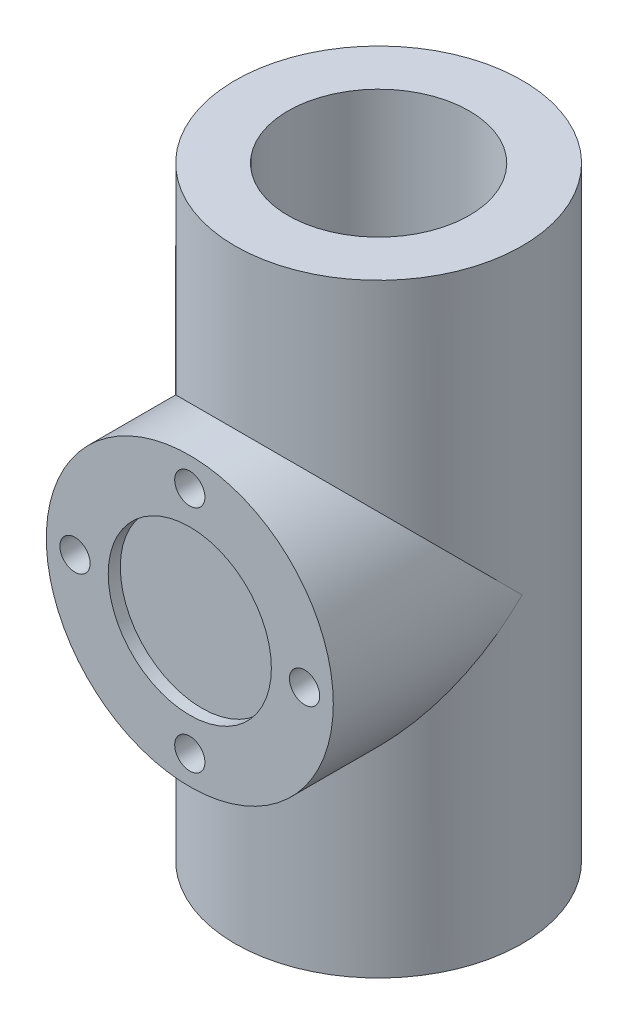
SolidWorks part; units mm, degrees
material "AISI 4340 Steel, normalized"
ref_plane "Front Plane" through (0, 0, 0) normal (0, 0, 1) x (1, 0, 0)
ref_plane "Top Plane" through (0, 0, 0) normal (0, 1, 0) x (1, 0, 0)
ref_plane "Right Plane" through (0, 0, 0) normal (1, 0, 0) x (0, 0, -1)
sketch "Sketch1" plane through (0, 0, 0) normal (0, 1, 0) x (1, 0, 0)
  circle A0 centre (0, 0) radius 47.5
  dimension "D1" = 95
extrude "Boss-Extrude1" add sketch "Sketch1" along normal mid plane 200
ref_plane "Plane1" through (0, 0, 62.5) normal (0, 0, 1) x (1, 0, 0)
sketch "Sketch2" plane through (0, 0, 62.5) normal (0, 0, 1) x (1, 0, 0)
  circle A0 centre (0, 0) radius 47.5
  dimension "D1" = 95
extrude "Boss-Extrude2" add sketch "Sketch2" against normal up to surface (62.5 mm away)
sketch "Sketch3" plane through (0, -100, 0) normal (0, -1, 0) x (1, 0, 0)
  circle A0 centre (0, 0) radius 30
  dimension "D1" = 60
extrude "Cut-Extrude1" cut sketch "Sketch3" against normal blind 200
sketch "Sketch4" plane through (0, 0, 62.5) normal (0, 0, 1) x (1, 0, 0)
  circle A0 centre (0, 0) radius 27
  dimension "D1" = 54
extrude "Cut-Extrude2" cut sketch "Sketch4" against normal blind 4
sketch "Sketch5" plane through (0, 0, 62.5) normal (0, 0, 1) x (1, 0, 0)
  circle A0 centre (0, 0) radius 38 construction
  circle A1 centre (0, 38) radius 5
  circle A2 centre (0.001, 0.001) radius 38 construction
  circle A3 centre (38.001, 0.001) radius 5
  circle A4 centre (0.002, 0) radius 38 construction
  circle A5 centre (0.002, -38) radius 5
  circle A6 centre (0.001, -0.001) radius 38 construction
  circle A7 centre (-37.999, -0.001) radius 5
  point P20 (0.001, 0)
  dimension "D1" = 76
  dimension "D2" = 10
  dimension "D3" = 4
extrude "Cut-Extrude3" cut sketch "Sketch5" against normal blind 20
